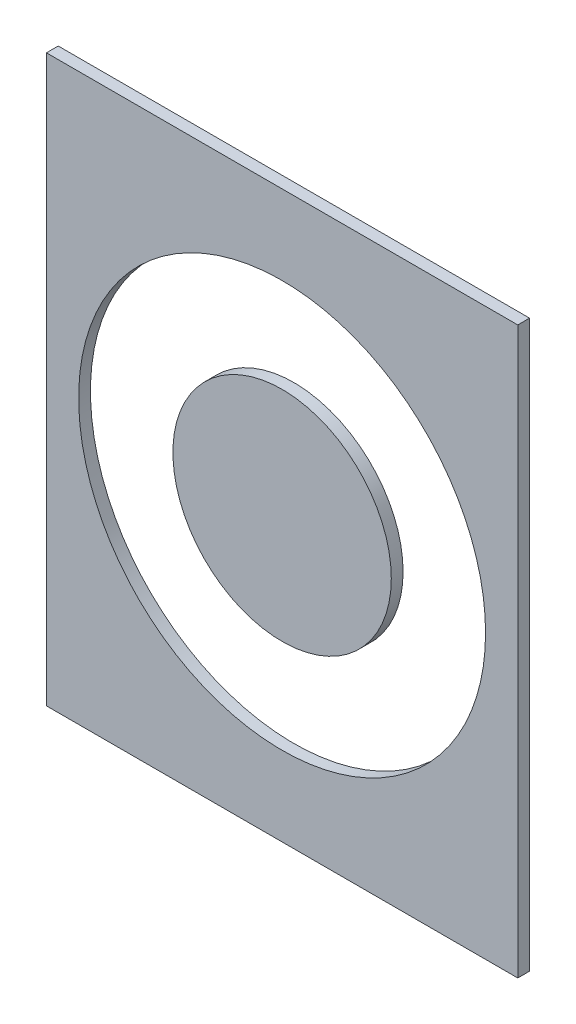
SolidWorks part; units mm, degrees
ref_plane "Plan de face" through (0, 0, 0) normal (0, 0, 1) x (1, 0, 0)
ref_plane "Plan de dessus" through (0, 0, 0) normal (0, 1, 0) x (1, 0, 0)
ref_plane "Plan de droite" through (0, 0, 0) normal (1, 0, 0) x (0, 0, -1)
sketch "Esquisse1" plane through (0, 0, 0) normal (0, 0, 1) x (1, 0, 0)
  line L1 (300, -360) -> (-300, -360)
  line L2 (300, -360) -> (300, 360)
  line L3 (300, 360) -> (-300, 360)
  line L4 (-300, -360) -> (-300, 360)
  line L5 (300, -360) -> (-300, 360) construction
  line L6 (300, 360) -> (-300, -360) construction
  point P0 (0, 0)
  dimension "D1" = 600
  dimension "D2" = 720
extrude "Boss.-Extru.1" add sketch "Esquisse1" along normal blind 15
sketch "Esquisse2" plane through (0, 0, 15) normal (0, 0, 1) x (1, 0, 0)
  circle A0 centre (0, 0) radius 259
  circle A1 centre (0, 0) radius 139
  dimension "D1" = 518
  dimension "D2" = 278
extrude "Enlèv. mat.-Extru.1" cut sketch "Esquisse2" against normal blind 15
